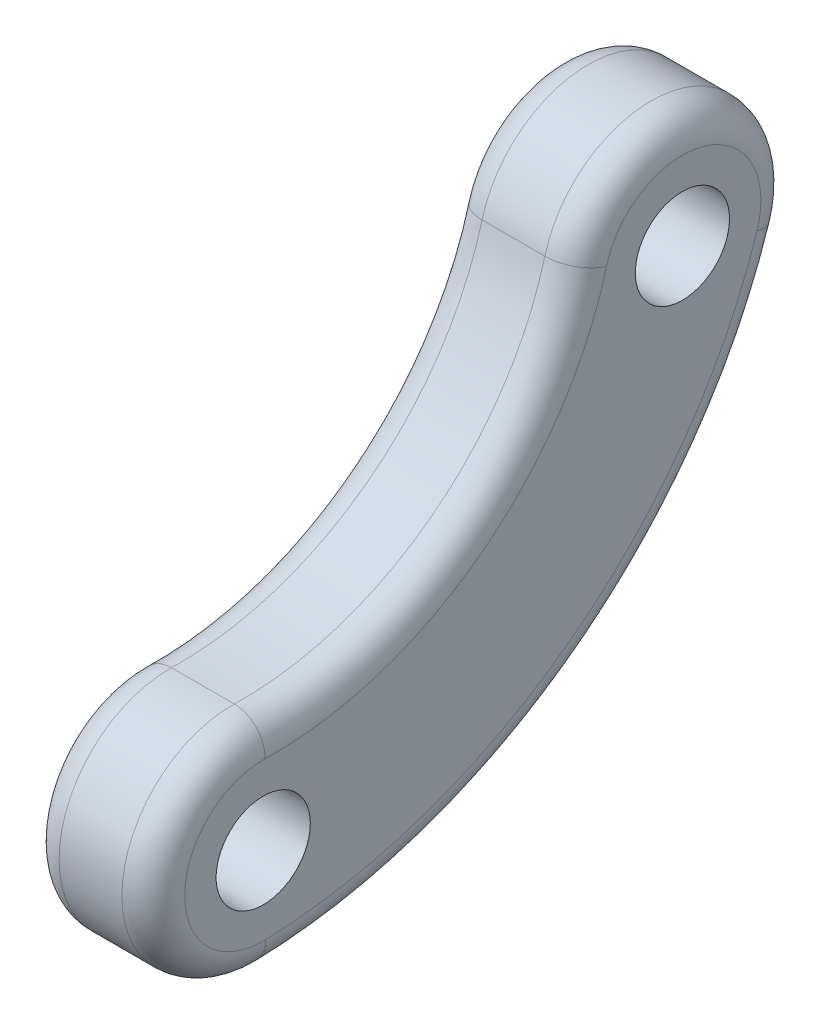
SolidWorks part; units mm, degrees
material "Alloy Steel"
ref_plane "Спереди" through (0, 0, 0) normal (0, 0, 1) x (1, 0, 0)
ref_plane "Сверху" through (0, 0, 0) normal (0, 1, 0) x (1, 0, 0)
ref_plane "Справа" through (0, 0, 0) normal (1, 0, 0) x (0, 0, -1)
other "Center of Mass"
sketch "Sketch1" plane through (0, 0, 0) normal (1, 0, 0) x (0, 0, -1)
  line L0 (0, 77.0459) -> (0, -152.6446) construction
  circle A0 centre (0, 0) radius 15
  arc A1 (33.277, -10.8462) -> (-33.8058, 9.0648) centre (0, 0) ccw
  circle A2 centre (-133.5, -100) radius 15
  arc A3 (-132.6946, -65.0093) -> (-132.4471, -134.9842) centre (-133.5, -100) ccw
  arc A4 (-33.8058, 9.0648) -> (-132.6946, -65.0093) centre (-130.3936, 34.9643) cw
  arc A6 (-132.4471, -134.9842) -> (33.277, -10.8462) centre (-137.8619, 44.9344) ccw
  dimension "D1" = 30
  dimension "D4" = 30
  dimension "D7" = 180
  dimension "D8" = 100
  dimension "D2" = 20
  dimension "D3" = 20
  dimension "D5" = 100
  dimension "D6" = 133.5
extrude "Boss-Extrude1" add sketch "Sketch1" along normal blind 40
fillet "Fillet1" radius 10 8 edges at (0, 33.5532, -9.959) (0, -99.1303, 29.9482) (0, -100.1238, 168.4998) (40, 33.5532, -9.959) (40, -99.1303, 29.9482) (40, -100.1238, 168.4998) (0, -45.0717, 70.4416) (40, -45.0717, 70.4416)
equation "\"D3@Sketch1\"=\"D2@Sketch1\""
equation "\"D4@Sketch1\"=\"D1@Sketch1\""
